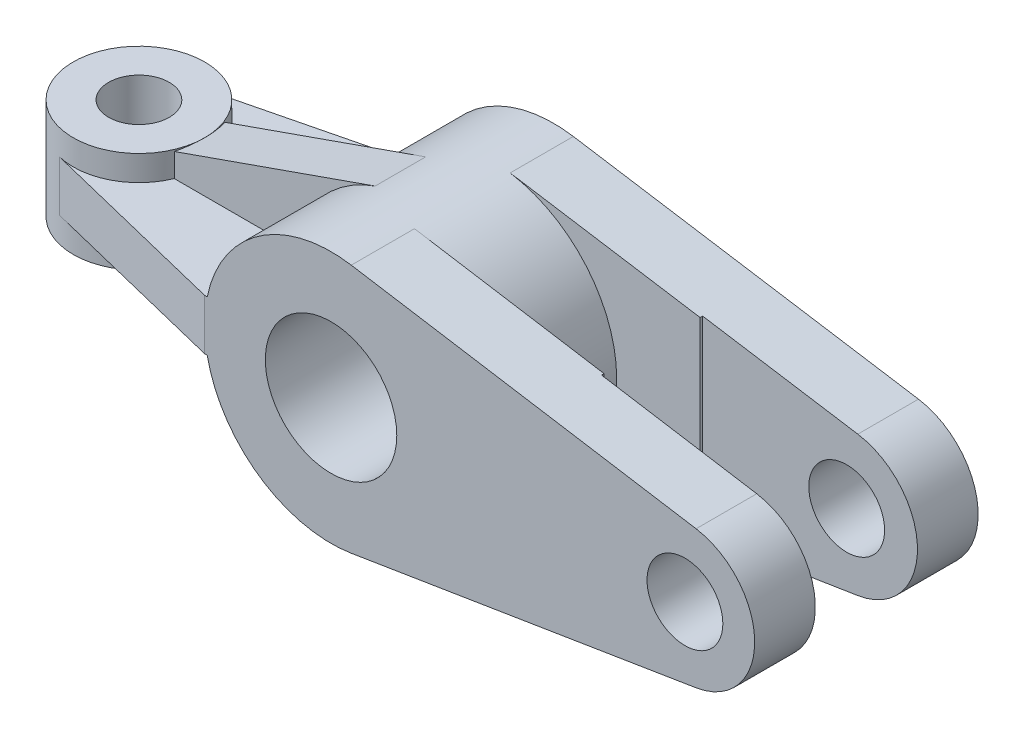
SolidWorks part; units mm, degrees
ref_plane "Front Plane" through (0, 0, 0) normal (0, 0, 1) x (1, 0, 0)
ref_plane "Top Plane" through (0, 0, 0) normal (0, 1, 0) x (1, 0, 0)
ref_plane "Right Plane" through (0, 0, 0) normal (1, 0, 0) x (0, 0, -1)
sketch "Sketch1" plane through (0, 0, 0) normal (0, 0, 1) x (1, 0, 0)
  circle A0 centre (0, 0) radius 25
  circle A1 centre (0, 0) radius 13
  dimension "D1" = 26
  dimension "D2" = 50
extrude "Boss-Extrude1" add sketch "Sketch1" along normal blind 44
sketch "Sketch2" plane through (0, 0, 0) normal (0, 0, 1) x (1, 0, 0)
  line L0 (0, 0) -> (70, 0) construction
  line L1 (3.9286, 24.6894) -> (72.2, 13.8261)
  line L2 (3.9286, -24.6894) -> (72.2, -13.8261)
  arc A0 (72.2, -13.8261) -> (72.2, 13.8261) centre (70, 0) ccw
  circle A1 centre (70, 0) radius 7.5
  circle A3 centre (0, 0) radius 25 construction
  arc A4 (3.9286, 24.6894) -> (3.9286, -24.6894) centre (0, 0) cw
  dimension "D1" = 15
  dimension "D2" = 28
  dimension "D3" = 70
extrude "Boss-Extrude2" add sketch "Sketch2" along normal blind 12.5
sketch "Sketch3" plane through (0, 0, 44) normal (0, 0, 1) x (1, 0, 0)
  line L0 (0, 0) -> (70, 0) construction
  line L1 (3.9994, 24.678) -> (72.2079, 13.6239)
  line L2 (3.9994, -24.678) -> (72.2079, -13.6239)
  circle A0 centre (70, 0) radius 7.5
  arc A1 (72.2079, -13.6239) -> (72.2079, 13.6239) centre (70, 0) ccw
  circle A2 centre (0, 0) radius 25 construction
  arc A3 (3.9994, 24.678) -> (3.9994, -24.678) centre (0, 0) cw
  dimension "D1" = 27.6032
  dimension "D2" = 15
extrude "Boss-Extrude3" add sketch "Sketch3" against normal blind 12.5
ref_plane "Plane1" through (91, 0, 0) normal (1, 0, 0) x (0, 0, -1)
sketch "Sketch5" plane through (91, 0, 0) normal (1, 0, 0) x (0, 0, -1)
  line L0 (-22, 25) -> (-22, -25) construction
  line L1 (-32, 25) -> (-12, 25)
  line L2 (-32, 25) -> (-32, -25)
  line L3 (-32, -25) -> (-12, -25)
  line L4 (-12, 25) -> (-12, -25)
  line L5 (0, 25) -> (-44, 25) construction
  line L6 (-44, -25) -> (0, -25) construction
  dimension "D1" = 10
  dimension "D2" = 20
extrude "Cut-Extrude1" cut sketch "Sketch5" against normal blind 49.5 contours L2 L3 L4 L1
sketch "Sketch6" plane through (0, 0, 0) normal (0, 1, 0) x (1, 0, 0)
  line L0 (-60, -22) -> (25, -22) construction
  line L1 (25, -31.5) -> (25, -12.5) construction
  line L2 (0, -44) -> (0, 0) construction
  line L3 (-25, -44) -> (3.9994, -44) construction
  circle A0 centre (-60, -22) radius 13
  circle A1 centre (-60, -22) radius 6
  point P9 (0, 0)
  dimension "D1" = 12
  dimension "D2" = 26
  dimension "D3" = 60
extrude "Boss-Extrude4" add sketch "Sketch6" along normal mid plane 20 separate body
ref_plane "Plane2" through (0, 0, 0) normal (0, 1, 0) x (1, 0, 0)
sketch "Sketch8" plane through (0, 0, 0) normal (0, 1, 0) x (1, 0, 0)
  line L0 (-63.1062, -9.3765) -> (-25, 0)
  line L1 (-21.3636, 0) -> (-21.3636, -44)
  line L2 (-25, -44) -> (-63.1062, -34.6235)
  line L3 (3.9286, 0) -> (-25, 0) construction
  line L4 (-25, -44) -> (3.9994, -44) construction
  line L5 (-21.3636, -44) -> (-25, -44)
  line L6 (-25, 0) -> (-21.3636, 0)
  circle A0 centre (-60, -22) radius 13 construction
  arc A1 (-63.1062, -9.3765) -> (-63.1062, -34.6235) centre (-60, -22) cw
  dimension "D1" = 3.6364
extrude "Boss-Extrude5" add sketch "Sketch8" along normal mid plane 10 contours L0 L6 L1 L5 L2 A1
ref_plane "Plane3" through (0, 0, 22) normal (0, 0, 1) x (1, 0, 0)
sketch "Sketch9" plane through (0, 0, 22) normal (0, 0, 1) x (1, 0, 0)
  line L0 (-47, 10) -> (-8.2788, 23.5894)
  arc A0 (3.9994, 24.678) -> (-24.4949, 5) centre (0, 0) ccw construction
rib "Rib2" sketch "Sketch9" sketch "Sketch9" thickness 10 extrusion direction parallel to sketch draft on no parameters "D1"=10
